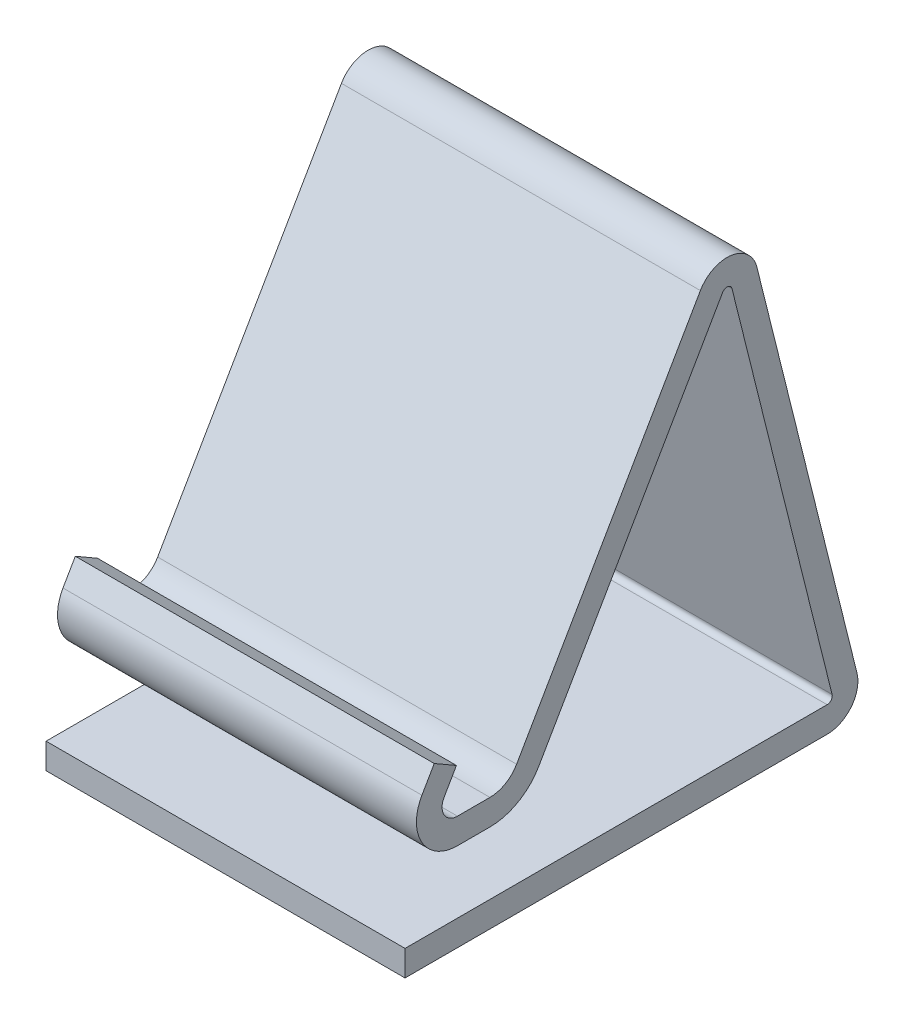
SolidWorks part; units mm, degrees
ref_plane "前视基准面" through (0, 0, 0) normal (0, 0, 1) x (1, 0, 0)
ref_plane "上视基准面" through (0, 0, 0) normal (0, 1, 0) x (1, 0, 0)
ref_plane "右视基准面" through (0, 0, 0) normal (1, 0, 0) x (0, 0, -1)
sketch "草图1" plane through (0, 0, 0) normal (1, 0, 0) x (0, 0, -1)
  line L0 (-14.9073, 7.4639) -> (-17.3092, 3.3036)
  line L1 (-14.7111, -1.1964) -> (-8.3714, -1.1964)
  line L2 (-3.1752, 1.8036) -> (32.6675, 63.885)
  line L3 (43.6854, 62.3365) -> (63.2087, -15.9671)
  line L4 (57.3869, -23.4187) -> (-24.9334, -23.4187)
  line L5 (40.0927, 76.7459) -> (40.0927, -76.3086) construction
  line L6 (-19.2374, 9.9639) -> (-21.6393, 5.8036)
  line L7 (-14.7111, -6.1964) -> (-8.3714, -6.1964)
  line L8 (1.1549, -0.6964) -> (36.9976, 61.385)
  line L9 (38.8339, 61.1269) -> (58.3572, -17.1767)
  line L10 (57.3869, -18.4187) -> (-24.9334, -18.4187)
  line L11 (-19.2374, 9.9639) -> (-14.9073, 7.4639)
  line L12 (-24.9334, -18.4187) -> (-24.9334, -23.4187)
  arc A0 (57.3869, -23.4187) -> (63.2087, -15.9671) centre (57.3869, -17.4187) ccw
  arc A1 (32.6675, 63.885) -> (43.6854, 62.3365) centre (37.8636, 60.885) cw
  arc A2 (-8.3714, -1.1964) -> (-3.1752, 1.8036) centre (-8.3714, 4.8036) ccw
  arc A3 (-14.7111, -1.1964) -> (-17.3092, 3.3036) centre (-14.7111, 1.8036) cw
  arc A4 (-14.7111, -6.1964) -> (-21.6393, 5.8036) centre (-14.7111, 1.8036) cw
  arc A5 (-8.3714, -6.1964) -> (1.1549, -0.6964) centre (-8.3714, 4.8036) ccw
  arc A6 (36.9976, 61.385) -> (38.8339, 61.1269) centre (37.8636, 60.885) cw
  arc A7 (57.3869, -18.4187) -> (58.3572, -17.1767) centre (57.3869, -17.4187) ccw
  point P9 (65.0666, -23.4187)
  point P15 (-4.9073, -1.1964)
  point P18 (-19.9073, -1.1964)
  dimension "D9" = 6
  dimension "D10" = 6
  dimension "D11" = 6
  dimension "D12" = 3
  dimension "D1" = 10
  dimension "D2" = 15
  dimension "D3" = 90
  dimension "D4" = 103.231
  dimension "D5" = 90
  dimension "D6" = 76
  dimension "D7" = 30
  dimension "D8" = 60
  dimension "D13" = 5
extrude "凸台-拉伸1" add sketch "草图1" along normal blind 70
